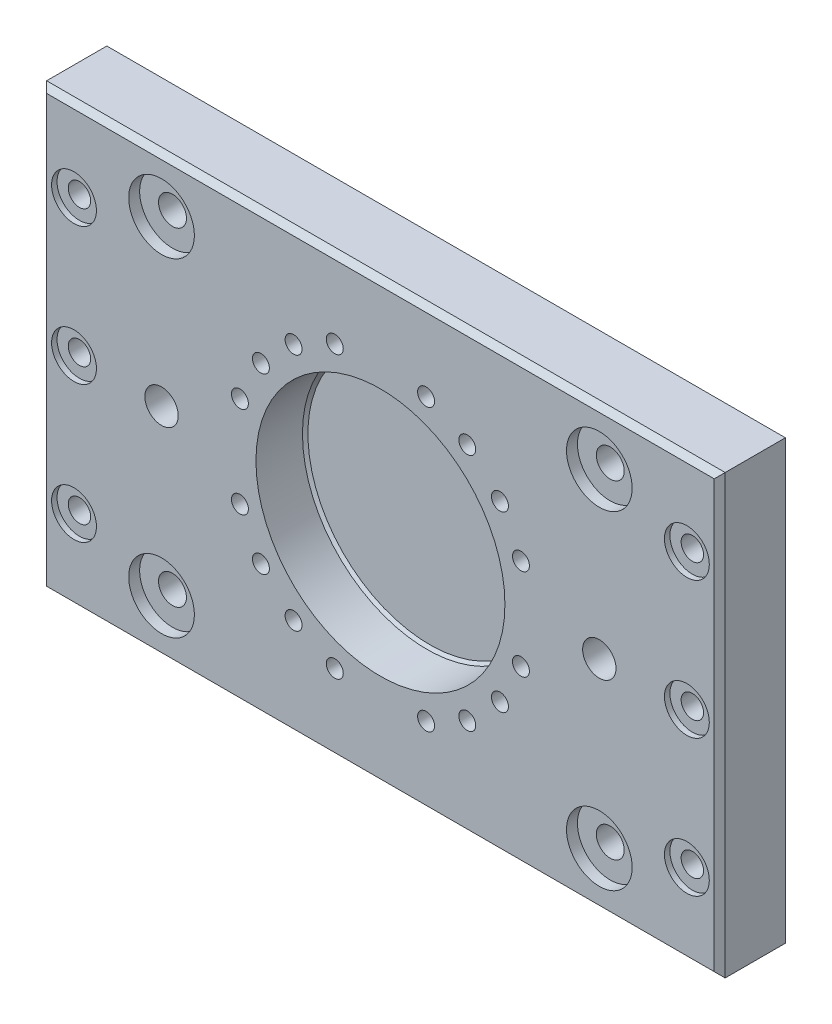
SolidWorks part; units mm, degrees
ref_plane "Спереди" through (0, 0, 0) normal (0, 0, 1) x (1, 0, 0)
ref_plane "Сверху" through (0, 0, 0) normal (0, 1, 0) x (1, 0, 0)
ref_plane "Справа" through (0, 0, 0) normal (1, 0, 0) x (0, 0, -1)
other "Configuration Table"
sketch "Эскиз1" plane through (0, 0, 0) normal (0, 0, 1) x (1, 0, 0)
  line L1 (-62, -40) -> (62, -40)
  line L2 (-62, -40) -> (-62, 40)
  line L3 (-62, 40) -> (62, 40)
  line L4 (62, -40) -> (62, 40)
  line L5 (-62, -40) -> (62, 40) construction
  line L6 (-62, 40) -> (62, -40) construction
  point P0 (0, 0)
  dimension "D1" = 124
  dimension "D2" = 80
extrude "Бобышка-Вытянуть1" add sketch "Эскиз1" along normal blind 12
sketch "Эскиз2" plane through (0, 0, 12) normal (0, 0, 1) x (1, 0, 0)
  circle A0 centre (0, 0) radius 22.75
  dimension "D1" = 45.5
extrude "Вырез-Вытянуть1" cut sketch "Эскиз2" against normal blind 9
sketch "Эскиз3" plane through (0, 0, 12) normal (0, 0, 1) x (1, 0, 0)
  line L0 (-40, 30) -> (-40, 0) construction
  line L1 (-40, 0) -> (-40, -30) construction
  line L2 (-40, 0) -> (0, 0) construction
  line L3 (0, 0) -> (40, 0) construction
  line L4 (40, 0) -> (40, 30) construction
  line L5 (40, 0) -> (40, -30) construction
  circle A0 centre (-40, 30) radius 2.55
  circle A1 centre (-40, 0) radius 3.05
  circle A2 centre (-40, -30) radius 2.55
  circle A3 centre (40, -30) radius 2.55
  circle A4 centre (40, 0) radius 3.05
  circle A5 centre (40, 30) radius 2.55
  dimension "D1" = 5.1
  dimension "D4" = 6.1
  dimension "D2" = 40
  dimension "D3" = 30
extrude "Вырез-Вытянуть2" cut sketch "Эскиз3" against normal through all
sketch "Эскиз4" plane through (0, 0, 12) normal (0, 0, 1) x (1, 0, 0)
  line L0 (-62, 40) -> (-62, -40) construction
  line L1 (62, -40) -> (62, 40) construction
  line L2 (-56, 25) -> (-56, 0) construction
  line L3 (-56, 0) -> (-56, -25) construction
  line L4 (56, 25) -> (56, 0) construction
  line L5 (56, 0) -> (56, -25) construction
  line L6 (-62, 0) -> (62, 0) construction
  circle A0 centre (-56, 25) radius 2.05
  circle A1 centre (-56, 0) radius 2.05
  circle A2 centre (-56, -25) radius 2.05
  circle A3 centre (56, -25) radius 2.05
  circle A4 centre (56, 0) radius 2.05
  circle A5 centre (56, 25) radius 2.05
  dimension "D1" = 4.1
  dimension "D2" = 6
  dimension "D3" = 6
  dimension "D4" = 25
extrude "Вырез-Вытянуть3" cut sketch "Эскиз4" against normal up to surface (12 mm away) up to face at (42.55, 30, 0)
chamfer "Фаска1" distance 0.5 angle 45 1 edges at (22.75, 0, 3)
sketch "Эскиз5" plane through (0, 0, 12) normal (0, 0, 1) x (1, 0, 0)
  line L0 (-8.3435, 25.6785) -> (0, 0) construction
  line L1 (0, 0) -> (0, 44.2232) construction
  circle A0 centre (0, 0) radius 27 construction
  circle A1 centre (-8.3435, 25.6785) radius 1.55
  circle A2 centre (0, 27) radius 1.55 [skipped]
  circle A3 centre (8.3435, 25.6785) radius 1.55
  circle A4 centre (15.8702, 21.8435) radius 1.55
  circle A5 centre (21.8435, 15.8702) radius 1.55
  circle A6 centre (25.6785, 8.3435) radius 1.55
  circle A7 centre (27, 0) radius 1.55 [skipped]
  circle A8 centre (25.6785, -8.3435) radius 1.55
  circle A9 centre (21.8435, -15.8702) radius 1.55
  circle A10 centre (15.8702, -21.8435) radius 1.55
  circle A11 centre (8.3435, -25.6785) radius 1.55
  circle A12 centre (0, -27) radius 1.55 [skipped]
  circle A13 centre (-8.3435, -25.6785) radius 1.55
  circle A14 centre (-15.8702, -21.8435) radius 1.55
  circle A15 centre (-21.8435, -15.8702) radius 1.55
  circle A16 centre (-25.6785, -8.3435) radius 1.55
  circle A17 centre (-27, 0) radius 1.55 [skipped]
  circle A18 centre (-25.6785, 8.3435) radius 1.55
  circle A19 centre (-21.8435, 15.8702) radius 1.55
  circle A20 centre (-15.8702, 21.8435) radius 1.55
  point P47 (0, 0)
  dimension "D1" = 54
  dimension "D2" = 3.1
  dimension "D3" = 18
  dimension "D4" = 20
extrude "Вырез-Вытянуть4" cut sketch "Эскиз5" against normal up to surface (12 mm away) up to face at (53.95, 25, 0)
sketch "Эскиз6" plane through (0, 0, 0) normal (0, 0, -1) x (-1, 0, 0)
  circle A0 centre (0, 0) radius 27 construction
  circle A1 centre (-8.3435, 25.6785) radius 3.25
  circle A2 centre (0, 27) radius 3.25 [skipped]
  circle A3 centre (8.3435, 25.6785) radius 3.25
  circle A4 centre (15.8702, 21.8435) radius 3.25
  circle A5 centre (21.8435, 15.8702) radius 3.25
  circle A6 centre (25.6785, 8.3435) radius 3.25
  circle A7 centre (27, 0) radius 3.25 [skipped]
  circle A8 centre (25.6785, -8.3435) radius 3.25
  circle A9 centre (21.8435, -15.8702) radius 3.25
  circle A10 centre (15.8702, -21.8435) radius 3.25
  circle A11 centre (8.3435, -25.6785) radius 3.25
  circle A12 centre (0, -27) radius 3.25 [skipped]
  circle A13 centre (-8.3435, -25.6785) radius 3.25
  circle A14 centre (-15.8702, -21.8435) radius 3.25
  circle A15 centre (-21.8435, -15.8702) radius 3.25
  circle A16 centre (-25.6785, -8.3435) radius 3.25
  circle A17 centre (-27, 0) radius 3.25 [skipped]
  circle A18 centre (-25.6785, 8.3435) radius 3.25
  circle A19 centre (-21.8435, 15.8702) radius 3.25
  circle A20 centre (-15.8702, 21.8435) radius 3.25
  point P47 (0, 0)
  dimension "D1" = 6.5
  dimension "D2" = 20
extrude "Вырез-Вытянуть5" cut sketch "Эскиз6" against normal blind 2.5
sketch "Эскиз7" plane through (0, 0, 12) normal (0, 0, 1) x (1, 0, 0)
  circle A0 centre (-40, -30) radius 6
  circle A2 centre (-40, 30) radius 6
  circle A3 centre (40, 30) radius 6
  circle A5 centre (40, -30) radius 6
  dimension "D1" = 12
extrude "Вырез-Вытянуть6" cut sketch "Эскиз7" against normal blind 2
sketch "Эскиз8" plane through (0, 0, 12) normal (0, 0, 1) x (1, 0, 0)
  circle A0 centre (-56, 25) radius 4.1
  circle A1 centre (-56, 0) radius 4.1
  circle A2 centre (-56, -25) radius 4.1
  circle A3 centre (56, -25) radius 4.1
  circle A4 centre (56, 0) radius 4.1
  circle A5 centre (56, 25) radius 4.1
  dimension "D1" = 8.2
extrude "Вырез-Вытянуть7" cut sketch "Эскиз8" against normal blind 1
chamfer "Фаска2" distance 1 angle 45 4 edges at (-62, 0, 12) (0, -40, 12) (62, 0, 12) (0, 40, 12)
